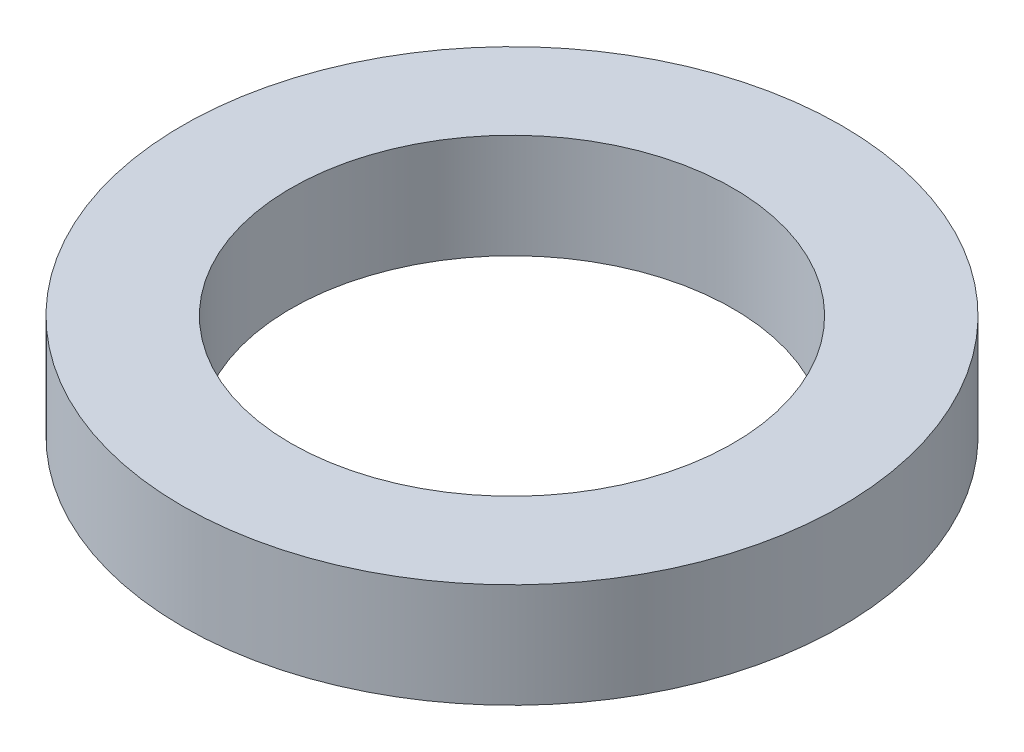
SolidWorks part; units mm, degrees
ref_plane "Front Plane" through (0, 0, 0) normal (0, 0, 1) x (1, 0, 0)
ref_plane "Top Plane" through (0, 0, 0) normal (0, 1, 0) x (1, 0, 0)
ref_plane "Right Plane" through (0, 0, 0) normal (1, 0, 0) x (0, 0, -1)
ref_plane "Plane1" through (0, 0, 0) normal (0, 0, -1) x (-1, 0, 0)
sketch "Sketch1" plane through (0, 0, 0) normal (0, 0, -1) x (-1, 0, 0)
  line L0 (-4.025, 1.9) -> (-6, 1.9)
  line L1 (-6, 1.9) -> (-6, 0)
  line L2 (-6, 0) -> (-4.025, 0)
  line L3 (-4.025, 0) -> (-4.025, 1.9)
  line L4 (0, 0) -> (0, 1.9) construction
revolve "Revolve1" add sketch "Sketch1" angle 360 about L4
